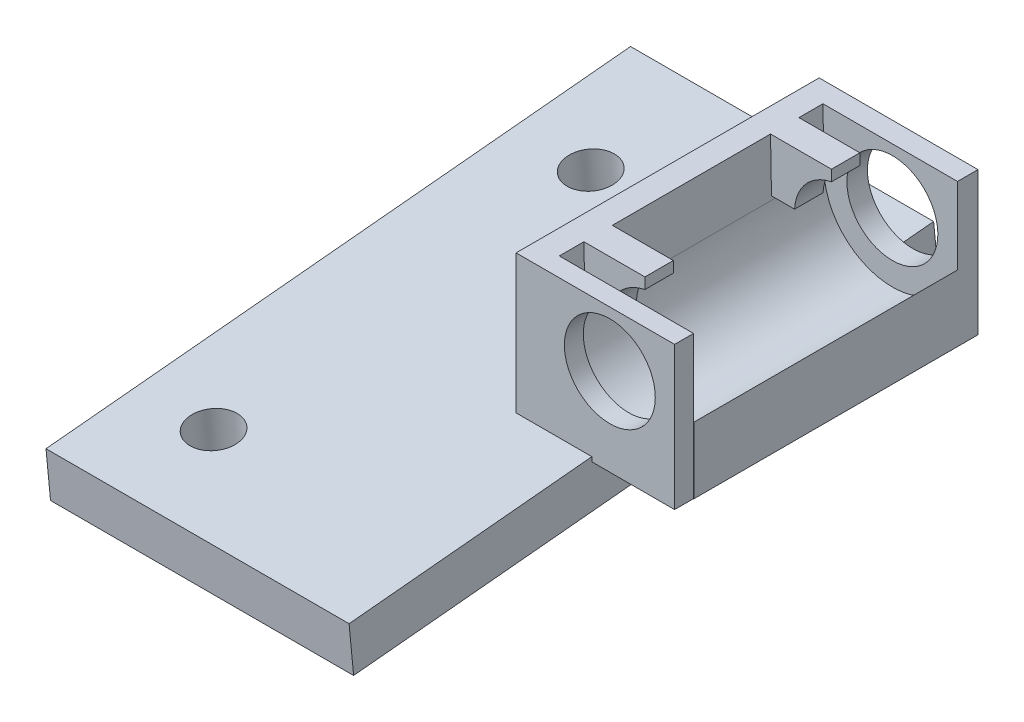
SolidWorks part; units mm, degrees
ref_plane "Front Plane" through (0, 0, 0) normal (0, 0, 1) x (1, 0, 0)
ref_plane "Top Plane" through (0, 0, 0) normal (0, 1, 0) x (1, 0, 0)
ref_plane "Right Plane" through (0, 0, 0) normal (1, 0, 0) x (0, 0, -1)
sketch "Sketch1" plane through (0, 0, 0) normal (0, 0, 1) x (1, 0, 0)
  line L0 (-215.5702, -0.3799) -> (-194.2711, -0.3799)
  line L1 (-194.2711, -0.3799) -> (-194.2711, 18.8069)
  line L2 (-194.2711, 18.8069) -> (-215.5702, 18.8069)
  line L3 (-215.5702, 18.8069) -> (-215.5702, -0.3799)
  line L4 (-444.5, -112.274) -> (444.5, -112.274) construction
  line L5 (-444.5, -112.274) -> (444.5, -112.274)
  line L6 (-212.1734, 11.1806) -> (-212.7401, 41.9083) construction
  line L7 (-212.1734, 11.1806) -> (-212.7401, 41.9083)
  arc A0 (-212.1734, 11.1806) -> (-194.0266, 9.437) centre (-203, 11.3498) ccw construction
  arc A1 (-212.1734, 11.1806) -> (-194.0266, 9.437) centre (-203, 11.3498) ccw
  circle A2 centre (-203, 11.3498) radius 6.096
  dimension "D1" = 19.1868
extrude "Boss-Extrude1" add sketch "Sketch1" against normal blind 38.1 contours A1 L7 L2 L3 L0 L1
sketch "Sketch2" plane through (0, 0, 0) normal (0, 0, 1) x (1, 0, 0)
  line L1 (-215.5702, -0.3799) -> (-194.3158, -0.3799)
  line L2 (-215.5702, -0.3799) -> (-215.5702, 18.8069)
  line L3 (-215.5702, 18.8069) -> (-194.3158, 18.8069)
  line L4 (-194.3158, -0.3799) -> (-194.3158, 18.8069)
  circle A0 centre (-203, 11.3498) radius 6.096
  dimension "D1" = 12.192
  dimension "D2" = 19.1868
  dimension "D3" = 21.2544
extrude "Boss-Extrude2" add sketch "Sketch2" along normal blind 2.54
sketch "Sketch3" plane through (0, 0, -38.1) normal (0, 0, -1) x (-1, 0, 0)
  line L1 (194.2711, -0.3799) -> (215.5702, -0.3799)
  line L2 (194.2711, -0.3799) -> (194.2711, 18.8069)
  line L3 (194.2711, 18.8069) -> (215.5702, 18.8069)
  line L4 (215.5702, -0.3799) -> (215.5702, 18.8069)
  circle A0 centre (203, 11.3498) radius 6.096
  dimension "D1" = 12.192
extrude "Boss-Extrude3" add sketch "Sketch3" against normal up to surface (2.75 mm away)
ref_plane "Plane1" through (-15.4811, 54.3786, 5.2147) normal (-0.2727, 0.9577, 0.0918) x (0.9621, 0.2714, 0.026)
sketch "Sketch4" plane through (-215.5702, 0, 0) normal (-1, 0, 0) x (0, 0, 1)
  line L0 (-38.1, 18.8069) -> (-38.1, -0.3799) construction
  line L1 (2.54, 18.8069) -> (2.54, -0.3799) construction
  line L4 (-32.131, 18.8069) -> (-32.131, 11.6949)
  line L5 (-28.321, 11.6949) -> (-28.321, 18.8069)
  line L6 (-38.1, 18.8069) -> (2.54, 18.8069) construction
  line L7 (-28.321, 18.8069) -> (-32.131, 18.8069)
  line L8 (-32.131, 11.6949) -> (-28.321, 11.6949)
  line L9 (-3.302, 11.6949) -> (-7.112, 11.6949)
  line L10 (-7.112, 11.6949) -> (-7.112, 18.8069)
  line L11 (-7.112, 18.8069) -> (-3.302, 18.8069)
  line L12 (-3.302, 18.8069) -> (-3.302, 11.6949)
  dimension "D1" = 3.81
  dimension "D2" = 5.969
  dimension "D3" = 7.112
  dimension "D4" = 7.112
  dimension "D5" = 3.81
  dimension "D6" = 5.842
extrude "Boss-Extrude4" add sketch "Sketch4" against normal blind 11.43
sketch "Sketch5" plane through (0, 0, 2.54) normal (0, 0, 1) x (1, 0, 0)
  circle A0 centre (-203, 11.3498) radius 6.096
  dimension "D1" = 12.192
extrude "Cut-Extrude1" cut sketch "Sketch5" against normal blind 48.006
ref_plane "Plane3" through (0, -2.0659, -0.1981) normal (0, 0.9954, 0.0955) x (1, 0, 0)
sketch "Sketch6" plane through (0, -2.0659, -0.1981) normal (0, 0.9954, 0.0955) x (1, 0, 0)
  line L1 (-246.0502, 43.5313) -> (-205.4102, 43.5313)
  line L2 (-246.0502, 43.5313) -> (-246.0502, -35.2087)
  line L3 (-246.0502, -35.2087) -> (-205.4102, -35.2087)
  line L4 (-205.4102, 43.5313) -> (-205.4102, -35.2087)
  circle A0 centre (-235.8571, 27.9259) radius 3.175
  circle A1 centre (-235.8571, -22.8741) radius 3.175
  dimension "D5" = 6.35
  dimension "D6" = 6.35
  dimension "D1" = 78.74
  dimension "D2" = 3.81
  dimension "D3" = 40.64
  dimension "D4" = 10.16
extrude "Boss-Extrude6" add sketch "Sketch6" against normal blind 3.81 and the other way blind 2.54
sketch "Sketch8" plane through (0, 0, -35.35) normal (0, 0, 1) x (1, 0, 0)
  line L0 (-208.2947, 3.8567) -> (-206.6184, 6.4438)
  line L1 (-197.3524, 9.055) -> (-194.2711, 8.5237)
  arc A0 (-208.2947, 3.8567) -> (-194.2711, 8.5237) centre (-203, 11.3498) ccw
  arc A1 (-206.6184, 6.4438) -> (-197.3524, 9.055) centre (-203, 11.3498) ccw
  circle A2 centre (-203, 11.3498) radius 6.096 construction
extrude "Cut-Extrude4" cut sketch "Sketch8" along normal blind 14.986
